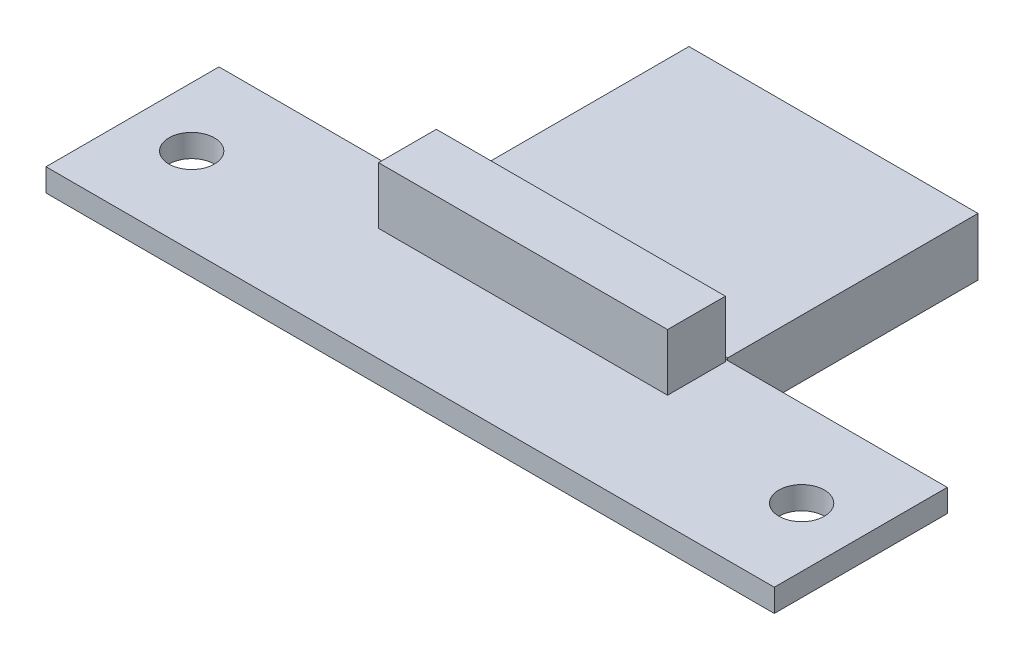
SolidWorks part; units mm, degrees
ref_plane "Спереди" through (0, 0, 0) normal (0, 0, 1) x (1, 0, 0)
ref_plane "Сверху" through (0, 0, 0) normal (0, 1, 0) x (1, 0, 0)
ref_plane "Справа" through (0, 0, 0) normal (1, 0, 0) x (0, 0, -1)
sketch "Sketch1" plane through (0, 0, 0) normal (0, 1, 0) x (1, 0, 0)
  line L1 (-16, 3.8) -> (16, 3.8)
  line L2 (-16, 3.8) -> (-16, -3.8)
  line L3 (-16, -3.8) -> (16, -3.8)
  line L4 (16, 3.8) -> (16, -3.8)
  line L5 (-16, 3.8) -> (16, -3.8) construction
  line L6 (-16, -3.8) -> (16, 3.8) construction
  point P0 (0, 0)
  dimension "D1" = 32
  dimension "D2" = 7.6
extrude "Boss-Extrude1" add sketch "Sketch1" along normal blind 1
sketch "Sketch2" plane through (0, 1, 0) normal (0, 1, 0) x (1, 0, 0)
  line L0 (-13.4, 0) -> (13.4, 0) construction
  circle A0 centre (-13.4, 0) radius 1
  circle A1 centre (13.4, 0) radius 1
  point P4 (0, 0)
  dimension "D1" = 2
  dimension "D2" = 26.8
extrude "Cut-Extrude1" cut sketch "Sketch2" against normal through all
sketch "Sketch3" plane through (0, 0, 0) normal (0, -1, 0) x (1, 0, 0)
  line L0 (-9.5, 0) -> (9.5, 0) construction
  line L1 (0, 1.1) -> (0, 0) construction
  line L2 (-10.3, 1.1) -> (-8.7, 1.1)
  line L3 (-10.3, 1.1) -> (-10.3, -1.1)
  line L4 (-10.3, -1.1) -> (-8.7, -1.1)
  line L5 (-8.7, 1.1) -> (-8.7, -1.1)
  line L6 (-10.3, 1.1) -> (-8.7, -1.1) construction
  line L7 (-10.3, -1.1) -> (-8.7, 1.1) construction
  line L8 (8.7, 1.1) -> (10.3, 1.1)
  line L9 (8.7, 1.1) -> (8.7, -1.1)
  line L10 (8.7, -1.1) -> (10.3, -1.1)
  line L11 (10.3, 1.1) -> (10.3, -1.1)
  line L12 (8.7, 1.1) -> (10.3, -1.1) construction
  line L13 (8.7, -1.1) -> (10.3, 1.1) construction
  line L14 (-0.8, 2.2) -> (0.8, 2.2)
  line L15 (-0.8, 2.2) -> (-0.8, 0)
  line L16 (-0.8, 0) -> (0.8, 0)
  line L17 (0.8, 2.2) -> (0.8, 0)
  line L18 (-0.8, 2.2) -> (0.8, 0) construction
  line L19 (-0.8, 0) -> (0.8, 2.2) construction
  point P3 (0, 1.1)
  point P4 (0, 0)
  dimension "D1" = 1.6
  dimension "D2" = 2.2
  dimension "D3" = 9.5
extrude "Boss-Extrude2" add sketch "Sketch3" along normal blind 1
sketch "Sketch4" plane through (0, 0, -3.8) normal (0, 0, -1) x (-1, 0, 0)
  line L0 (0, -0.17) -> (0, 0) construction
  line L1 (-6.35, 1.1) -> (6.35, 1.1)
  line L2 (-6.35, 1.1) -> (-6.35, -1.44)
  line L3 (-6.35, -1.44) -> (6.35, -1.44)
  line L4 (6.35, 1.1) -> (6.35, -1.44)
  line L5 (-6.35, 1.1) -> (6.35, -1.44) construction
  line L6 (-6.35, -1.44) -> (6.35, 1.1) construction
  line L8 (-16, 1) -> (16, 1) construction
  point P0 (0, -0.17)
  dimension "D1" = 2.54
  dimension "D2" = 12.7
  dimension "D3" = 0.1
extrude "Boss-Extrude3" add sketch "Sketch4" along normal blind 11
sketch "Sketch5" plane through (0, 1, 0) normal (0, 1, 0) x (1, 0, 0)
  line L0 (-6.35, 14.8) -> (-6.35, 3.8) construction
  line L1 (-6.35, 1.16) -> (6.35, 1.16)
  line L2 (-6.35, 1.16) -> (-6.35, 3.7)
  line L3 (-6.35, 3.7) -> (6.35, 3.7)
  line L4 (6.35, 1.16) -> (6.35, 3.7)
  line L5 (-6.35, 1.16) -> (6.35, 3.7) construction
  line L6 (-6.35, 3.7) -> (6.35, 1.16) construction
  line L7 (6.35, 14.8) -> (6.35, 3.8) construction
  line L8 (-6.35, 3.8) -> (-16, 3.8) construction
  point P0 (0, 2.43)
  dimension "D1" = 2.54
  dimension "D2" = 0.1
extrude "Boss-Extrude4" add sketch "Sketch5" along normal blind 2.5
